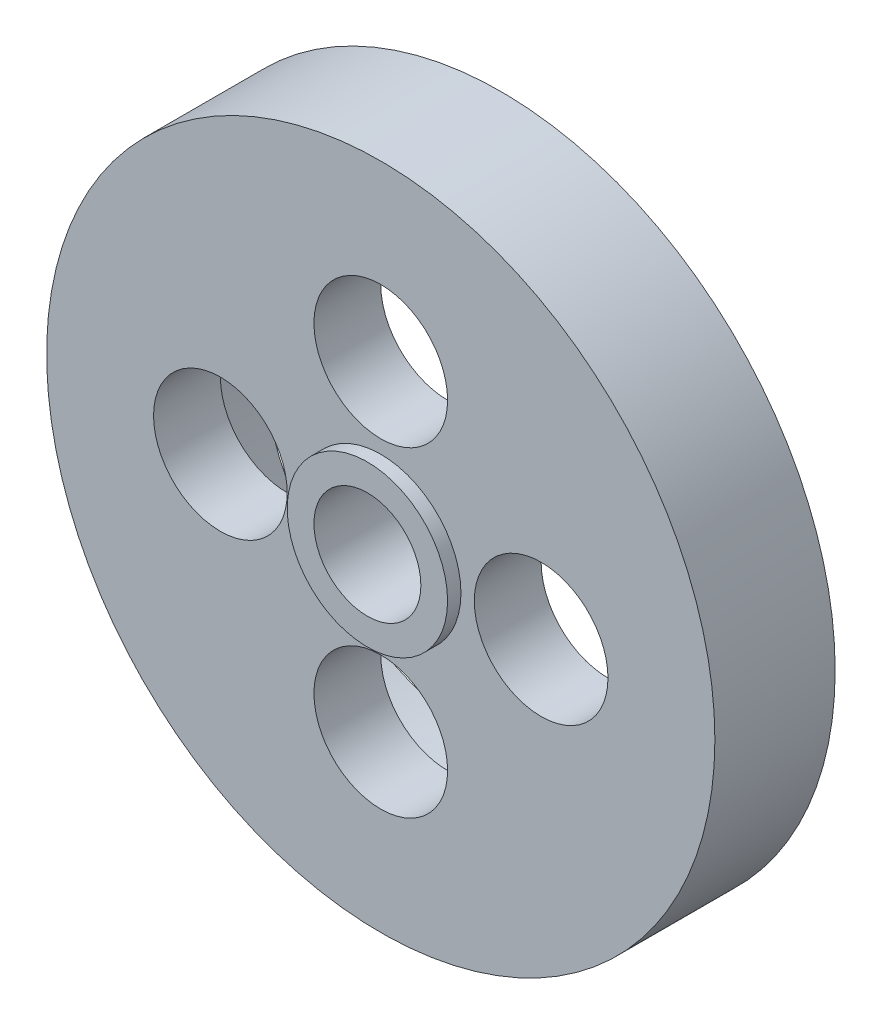
SolidWorks part; units mm, degrees
ref_plane "Front Plane" through (0, 0, 0) normal (0, 0, 1) x (1, 0, 0)
ref_plane "Top Plane" through (0, 0, 0) normal (0, 1, 0) x (1, 0, 0)
ref_plane "Right Plane" through (0, 0, 0) normal (1, 0, 0) x (0, 0, -1)
sketch "Sketch1" plane through (0, 0, 0) normal (0, 0, 1) x (1, 0, 0)
  circle A0 centre (0, 0) radius 25
  dimension "D1" = 50
extrude "Boss-Extrude2" add sketch "Sketch1" along normal blind 9
sketch "Sketch11" plane through (0, 0, 0) normal (0, 0, -1) x (-1, 0, 0)
  circle A0 centre (0, 0) radius 4
  circle A1 centre (0, 0) radius 6
  circle A2 centre (0, 0) radius 12 construction
  circle A3 centre (0, 12) radius 5
  circle A4 centre (12, 0) radius 5
  circle A5 centre (0, -12) radius 5
  circle A6 centre (-12, 0) radius 5
  point P16 (0, 0)
  dimension "D1" = 8
  dimension "D2" = 12
  dimension "D3" = 24
  dimension "D4" = 10
  dimension "D5" = 4
extrude "Cut-Extrude9" cut sketch "Sketch11" against normal up to next contours A3 | A4 | A5 | A6
sketch "Sketch12" plane through (0, 0, 0) normal (0, 0, -1) x (-1, 0, 0)
  circle A0 centre (0, 0) radius 4
  circle A1 centre (0, 0) radius 6
  circle A2 centre (0, 0) radius 18
  point P5 (0, 0)
  dimension "D1" = 8
  dimension "D2" = 12
  dimension "D3" = 36
extrude "Cut-Extrude11" cut sketch "Sketch12" against normal blind 9 contours A0
sketch "Sketch14" plane through (0, 0, 0) normal (0, 0, -1) x (-1, 0, 0)
  circle A0 centre (0, 0) radius 18
  dimension "D1" = 36
extrude "Cut-Extrude12" cut sketch "Sketch14" against normal blind 4
sketch "Sketch15" plane through (0, 0, 9) normal (0, 0, 1) x (1, 0, 0)
  circle A0 centre (0, 0) radius 6
  circle A1 centre (0, 0) radius 4
  dimension "D1" = 12
  dimension "D2" = 8
extrude "Boss-Extrude4" add sketch "Sketch15" along normal blind 1
